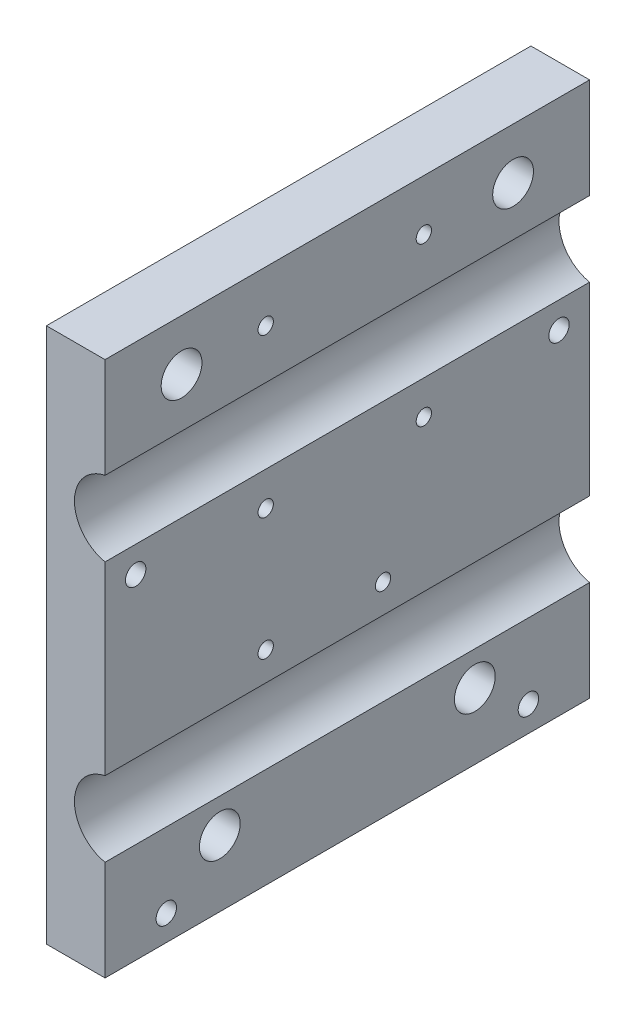
SolidWorks part; units mm, degrees
material "ABS"
ref_plane "Front Plane" through (0, 0, 0) normal (0, 0, 1) x (1, 0, 0)
ref_plane "Top Plane" through (0, 0, 0) normal (0, 1, 0) x (1, 0, 0)
ref_plane "Right Plane" through (0, 0, 0) normal (1, 0, 0) x (0, 0, -1)
sketch "Sketch1" plane through (0, 0, 0) normal (0, 0, 1) x (1, 0, 0)
  line L2 (0, 0) -> (0, -105)
  line L16 (0, 0) -> (-11.5, 0)
  line L17 (-11.5, 0) -> (-11.5, -105)
  line L18 (-11.5, -105) -> (0, -105)
  line L19 (-56.1833, -52.5) -> (48.7099, -52.5) construction
  circle A2 centre (1.5, -27) radius 7.5
  circle A3 centre (1.5, -78) radius 7.5
  point P11 (0, -52.5)
  dimension "D3" = 11.5
  dimension "D6" = 25.5
  dimension "D2" = 51
  dimension "D4" = 15
  dimension "D5" = 1.5
  dimension "D10" = 105
extrude "Boss-Extrude1" add sketch "Sketch1" along normal blind 95 contours L17 L19 L2 A2 L16 | L19 L17 L18 L2 A3
sketch "Sketch2" plane through (0, 0, 0) normal (1, 0, 0) x (0, 0, -1)
  line L0 (-47.5, 2.9897) -> (-47.5, -94.3027) construction
  line L1 (-95, 0) -> (0, 0) construction
  line L3 (-95, -105) -> (0, -105) construction
  circle A4 centre (-83, -100) radius 2
  circle A5 centre (-12, -100) radius 2
  point P4 (-47.5, 0)
  dimension "D5" = 4
  dimension "D6" = 5
extrude "Cut-Extrude1" cut sketch "Sketch2" against normal through all
sketch "Esquisse2" plane through (0, 0, 0) normal (1, 0, 0) x (0, 0, -1)
  line L0 (0, -34.3485) -> (0, -70.6515) construction
  line L1 (-95, 0) -> (0, 0) construction
  line L2 (-95, -34.3485) -> (-95, -70.6515) construction
  circle A0 centre (-6, -39.5) radius 2
  circle A1 centre (-89, -39.5) radius 2
  dimension "D1" = 4
  dimension "D2" = 6
  dimension "D3" = 39.5
  dimension "D4" = 6
extrude "Enlèv. mat.-Extru.2" cut sketch "Esquisse2" against normal through all
sketch "Esquisse3" plane through (-11.5, 0, 0) normal (-1, 0, 0) x (0, 0, 1)
  line L0 (95, 0) -> (95, -105) construction
  line L1 (95, 0) -> (0, 0) construction
  circle A0 centre (80, -10) radius 4
  circle A1 centre (15, -10) radius 4
  circle A4 centre (72.5, -92) radius 4
  circle A5 centre (22.5, -92) radius 4
  circle A6 centre (15, -45) radius 4 [skipped]
  circle A7 centre (80, -45) radius 4 [skipped]
  dimension "D1" = 8
  dimension "D2" = 15
  dimension "D3" = 10
  dimension "D6" = 65
  dimension "D8" = 7.5
  dimension "D9" = 82
  dimension "D11" = 50
  dimension "D4" = 2
  dimension "D5" = 2
  dimension "D10" = 2
extrude "Enlèv. mat.-Extru.3CNC" cut sketch "Esquisse3" against normal through all
ref_plane "Plan1" through (0, 0, 47.5) normal (0, 0, 1) x (1, 0, 0)
ref_plane "Plan2" through (0, -52.5, 0) normal (0, 1, 0) x (1, 0, 0)
sketch "Esquisse4" plane through (0, 0, 0) normal (1, 0, 0) x (0, 0, -1)
  line L0 (-47.5, 6.325) -> (-47.5, -6.325) construction
  line L1 (6.325, -52.5) -> (-6.325, -52.5) construction
  circle A0 centre (-32.5, -10) radius 1.5
  circle A1 centre (-63.5, -10) radius 1.5
  circle A2 centre (-63.5, -41) radius 1.5
  circle A3 centre (-32.5, -41) radius 1.5
  circle A4 centre (-40.5, -65) radius 1.5
  circle A5 centre (-63.5, -65) radius 1.5
  dimension "D1" = 15
  dimension "D2" = 42.5
  dimension "D3" = 3
  dimension "D6" = 31
  dimension "D7" = 31
  dimension "D8" = 8
  dimension "D9" = 55
  dimension "D11" = 23
  dimension "D4" = 2
  dimension "D5" = 2
  dimension "D10" = 2
extrude "Enlèv. mat.-Extru.4-3Dprinter" cut sketch "Esquisse4" against normal through all
